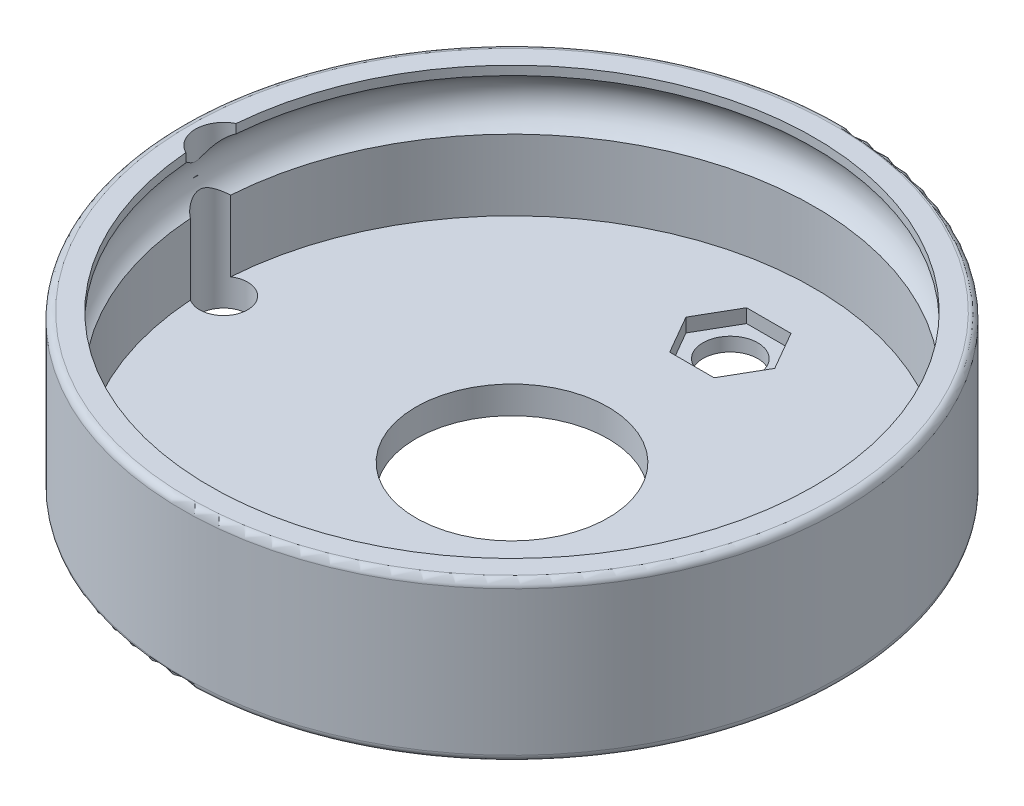
SolidWorks part; units mm, degrees
ref_plane "前视基准面" through (0, 0, 0) normal (0, 0, 1) x (1, 0, 0)
ref_plane "上视基准面" through (0, 0, 0) normal (0, 1, 0) x (1, 0, 0)
ref_plane "右视基准面" through (0, 0, 0) normal (1, 0, 0) x (0, 0, -1)
sketch "草图1" plane through (0, 0, 0) normal (0, 1, 0) x (1, 0, 0)
  circle A0 centre (0, 0) radius 20
  circle A1 centre (0, 0) radius 22
  circle A2 centre (0, 0) radius 25
  dimension "D1" = 44
sketch "草图2" plane through (0, 0, 0) normal (0, 0, 1) x (1, 0, 0)
  line L0 (0, 0) -> (24, 0)
  line L1 (25, 0) -> (-25, 0) construction
  line L2 (24, 0) -> (24, 11.5)
  line L3 (24, 11.5) -> (22, 11.5)
  line L4 (22, 11.5) -> (22, 2)
  line L5 (22, 2) -> (0, 2)
  line L6 (0, 2) -> (0, 0)
  line L7 (0, 2) -> (7, 2)
  line L8 (7, 2) -> (7, 0)
  circle A0 centre (21, 9) radius 2.1
  point P8 (21, 9)
  dimension "D4" = 11.5
  dimension "D5" = 4.2
  dimension "D1" = 2
  dimension "D2" = 2.5
  dimension "D3" = 1
  dimension "D6" = 2
  dimension "D7" = 24
  dimension "D8" = 7
revolve "旋转1" add sketch "草图2" angle 360 about L6
fillet "圆角1" radius 0.5 2 edges at (-24, 0, 0) (-24, 11.5, 0)
sketch "草图7" plane through (0, 0, 0) normal (0, -1, 0) x (1, 0, 0)
  line L0 (0, 0) -> (10.9, 0)
  dimension "D1" = 10.9
sketch "草图11" plane through (0, 11.5, 0) normal (0, 1, 0) x (1, 0, 0)
  circle A0 centre (0, 0) radius 22 construction
  circle A1 centre (-21, 0) radius 2.05
  point P0 (-22, 0)
  point P1 (-21, 0)
  dimension "D1" = 1
extrude "切除-拉伸3" cut sketch "草图11" against normal blind 3
sketch "草图13" plane through (0, 2, 0) normal (0, 1, 0) x (1, 0, 0)
  circle A1 centre (-21, 0) radius 1.75
  dimension "D1" = 3.5
extrude "切除-拉伸6" cut sketch "草图13" against normal through all and the other way blind 6
sketch "草图15" plane through (0, 2, 0) normal (0, 1, 0) x (1, 0, 0)
  line L5 (10.9, 0) -> (-9.6, 0)
  line L6 (31.4, -10.5) -> (-9.6, -10.5)
  line L22 (31.4, -10.5) -> (31.4, 10.5)
  line L23 (31.4, 10.5) -> (-9.6, 10.5)
  line L24 (-9.6, -10.5) -> (-9.6, 10.5)
  line L25 (31.4, -10.5) -> (-9.6, 10.5) construction
  line L26 (31.4, 10.5) -> (-9.6, -10.5) construction
  line L27 (-9.6, -10.5) -> (31.4, -10.5)
  line L28 (-9.6, -10.5) -> (-9.6, -18.5)
  line L29 (-9.6, -18.5) -> (31.4, -18.5)
  line L30 (31.4, -10.5) -> (31.4, -18.5)
  line L31 (-2.8332, -15.5) -> (-1.2166, -18.3)
  line L32 (-1.2166, -18.3) -> (2.0166, -18.3)
  line L33 (2.0166, -18.3) -> (3.6332, -15.5)
  line L34 (3.6332, -15.5) -> (2.0166, -12.7)
  line L35 (2.0166, -12.7) -> (-1.2166, -12.7)
  line L36 (-1.2166, -12.7) -> (-2.8332, -15.5)
  line L37 (-1.2166, 12.7) -> (-2.8332, 15.5)
  line L38 (2.0166, 12.7) -> (-1.2166, 12.7)
  line L39 (3.6332, 15.5) -> (2.0166, 12.7)
  line L40 (2.0166, 18.3) -> (3.6332, 15.5)
  line L41 (-1.2166, 18.3) -> (2.0166, 18.3)
  line L42 (-2.8332, 15.5) -> (-1.2166, 18.3)
  circle A0 centre (0.4, -15.5) radius 2.8 construction
  circle A1 centre (0.4, 15.5) radius 2.8 construction
  point P0 (10.9, 0)
  point P9 (0.4, -15.5)
  dimension "D2" = 5.6
  dimension "D1" = 10
  dimension "D3" = 3
  dimension "D4" = 8
extrude "切除-拉伸7" cut sketch "草图15" against normal blind 1 contours L42 L37 L38 L39 L40 L41 | L35 L36 L31 L32 L33 L34
sketch "草图16" plane through (0, 1, 0) normal (0, 1, 0) x (1, 0, 0)
  circle A2 centre (0.4, 15.5) radius 2
  circle A3 centre (0.4, -15.5) radius 2
extrude "切除-拉伸8" cut sketch "草图16" against normal blind 1
